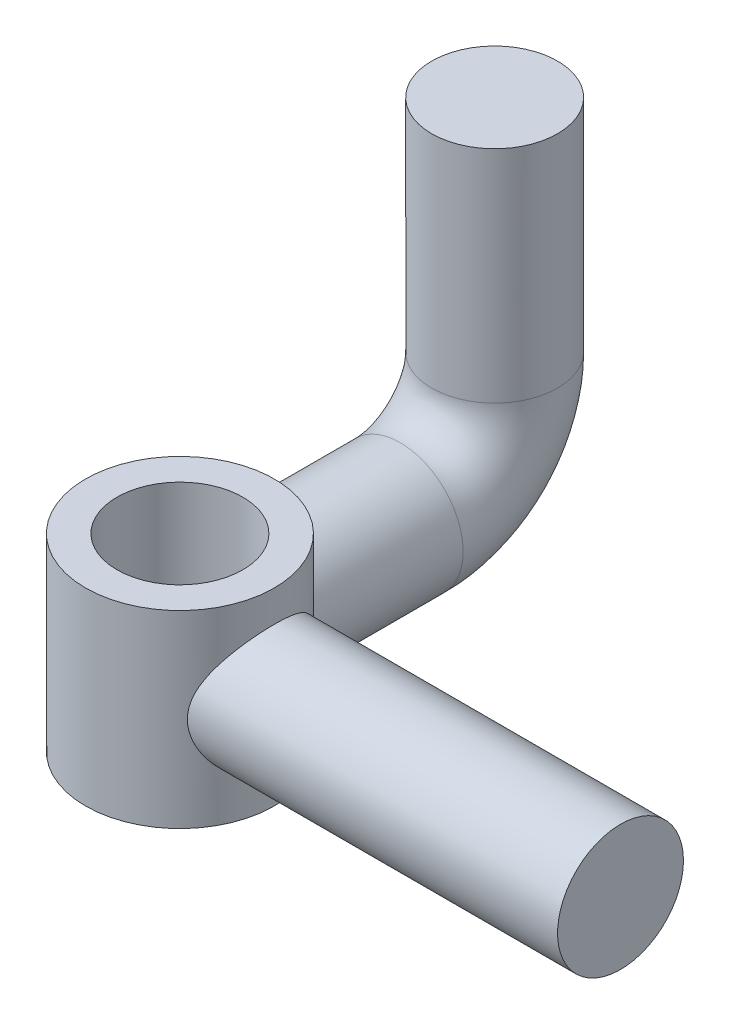
SolidWorks part; units mm, degrees
ref_plane "Front Plane" through (0, 0, 0) normal (0, 0, 1) x (1, 0, 0)
ref_plane "Top Plane" through (0, 0, 0) normal (0, 1, 0) x (1, 0, 0)
ref_plane "Right Plane" through (0, 0, 0) normal (1, 0, 0) x (0, 0, -1)
sketch "Sketch1" plane through (0, 0, 0) normal (0, 1, 0) x (1, 0, 0)
  circle A0 centre (0, 0) radius 1.5
  circle A1 centre (0, 0) radius 1
  dimension "D1" = 2
  dimension "D2" = 3
extrude "Boss-Extrude1" add sketch "Sketch1" against normal blind 3 contours A0
sketch "Sketch2" plane through (0, 0, 0) normal (1, 0, 0) x (0, 0, -1)
  line L0 (1.5, -1.5) -> (3.5, -1.5)
  line L1 (1.5, -3) -> (1.5, 0) construction
  line L2 (5, 0) -> (5, 3.5)
  arc A0 (5, 0) -> (3.5, -1.5) centre (3.5, 0) cw
  point P7 (5, -1.5)
  dimension "D3" = 1.5
  dimension "D1" = 5
  dimension "D2" = 3.5
ref_plane "Plane1" through (0, 3.5, 0) normal (0, 1, 0) x (1, 0, 0)
sketch "Sketch3" plane through (0, 3.5, 0) normal (0, 1, 0) x (1, 0, 0)
  circle A0 centre (0, 5) radius 1
  dimension "D1" = 2
sweep "Sweep1" add profiles "Sketch3" path "Sketch2"
sketch "Sketch4" plane through (0, 0, -1.5) normal (0, 0, 1) x (1, 0, 0)
  circle A0 centre (0, -1.5) radius 1 construction
  circle A1 centre (0, -1.5) radius 1
extrude "Boss-Extrude4" add sketch "Sketch4" along normal up to surface
ref_plane "Plane2" through (7, 0, 0) normal (1, 0, 0) x (0, 0, -1)
sketch "Sketch6" plane through (7, 0, 0) normal (1, 0, 0) x (0, 0, -1)
  line L0 (-1.5, 0) -> (-1.5, -3) construction
  circle A0 centre (0, -1.5) radius 1
  point P2 (-1.5, -1.5)
  dimension "D1" = 2
extrude "Boss-Extrude5" add sketch "Sketch6" against normal up to surface (5.882 mm away) contours A0
equation "\"innerDia\"= 1mm"
equation "\"outerDia\"= 1.5mm"
equation "\"axelDia\"= 0.9mm"
equation "\"axelLen\"= 7mm"
